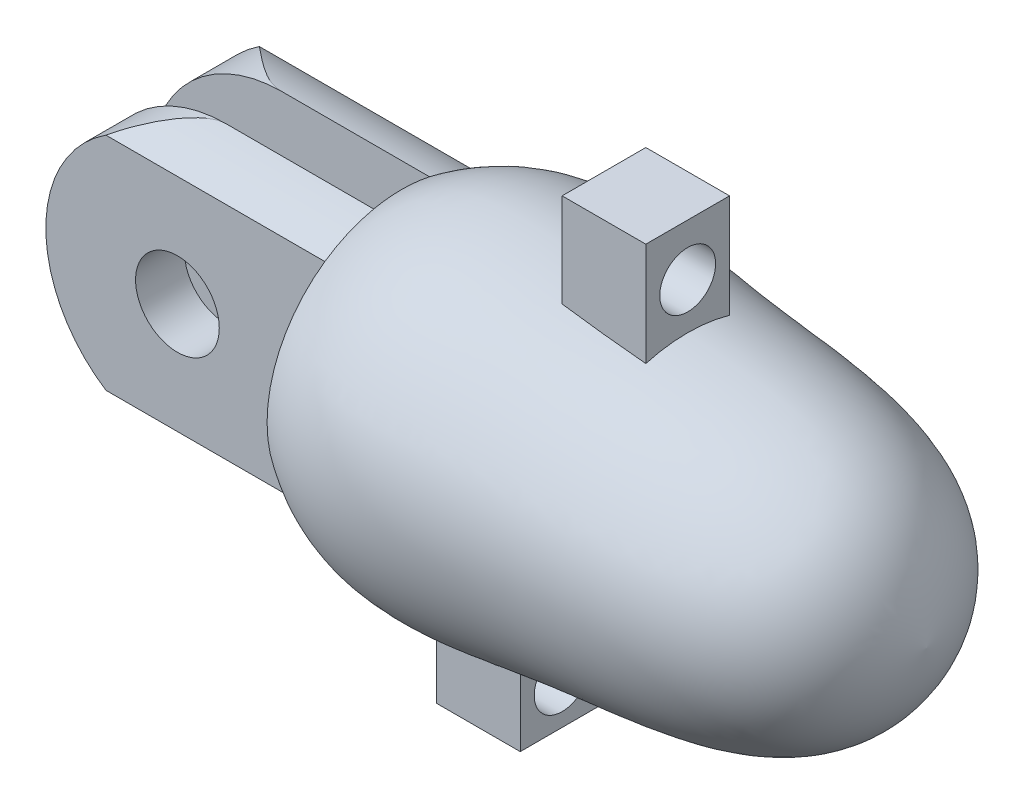
SolidWorks part; units mm, degrees
ref_plane "Front" through (0, 0, 0) normal (0, 0, 1) x (1, 0, 0)
ref_plane "Top" through (0, 0, 0) normal (0, 1, 0) x (1, 0, 0)
ref_plane "Right" through (0, 0, 0) normal (1, 0, 0) x (0, 0, -1)
sketch "Sketch1" plane through (0, 0, 0) normal (0, 0, 1) x (1, 0, 0)
  line L0 (-34.2752, 0) -> (65.3865, 0) construction
  line L1 (-17.5039, 9.6421) -> (-17.5039, 0)
  line L2 (-17.5039, 0) -> (20.1151, 0)
  spline S0 degree 3 poles (-17.5039, 9.6421) (-12.038, 13.468) (1.7207, 9.9869) (18.6749, 10.7604) (20.1151, 0) knots 0 0 0 0 0.417252 1 1 1 1
revolve "Revolve1" add sketch "Sketch1" angle 360 about L0
sketch "Sketch2" plane through (-17.5039, 0, 0) normal (-1, 0, 0) x (0, 0, 1)
  line L1 (-5.5, 10) -> (5.5, 10)
  line L2 (-5.5, 10) -> (-5.5, -10)
  line L3 (-5.5, -10) -> (5.5, -10)
  line L4 (5.5, 10) -> (5.5, -10)
  line L5 (-5.5, 10) -> (5.5, -10) construction
  line L6 (-5.5, -10) -> (5.5, 10) construction
  point P0 (0, 0)
  dimension "D1" = 20
  dimension "D2" = 11
extrude "Boss-Extrude1" add sketch "Sketch2" along normal blind 20
sketch "Sketch3" plane through (-17.5039, 0, 0) normal (-1, 0, 0) x (0, 0, 1)
  circle A0 centre (0, 0) radius 9.6421
  circle A1 centre (0, 0) radius 15
  arc A2 (-5.5, 7.9196) -> (-5.5, -7.9196) centre (0, 0) ccw construction
  dimension "D1" = 30
extrude "Cut-Extrude1" cut sketch "Sketch3" along normal through all
sketch "Sketch4" plane through (0, 0, 0) normal (0, 1, 0) x (1, 0, 0)
  line L0 (-37.5039, 5.5) -> (-37.5039, -5.5) construction
  line L5 (-37.5039, 2) -> (-17.5039, 2)
  line L6 (-37.5039, 2) -> (-37.5039, -2)
  line L7 (-37.5039, -2) -> (-17.5039, -2)
  line L8 (-17.5039, 2) -> (-17.5039, -2)
  line L9 (-17.5039, -5.5) -> (-17.5039, 5.5) construction
  dimension "D1" = 3.5
  dimension "D2" = 3.5
extrude "Cut-Extrude2" cut sketch "Sketch4" against normal through all both and the other way through all
sketch "Sketch6" plane through (0, 0, -2) normal (0, 0, 1) x (1, 0, 0)
  line L0 (-17.5039, -9.4324) -> (-37.5039, -9.4324) construction
  line L1 (-37.5039, 9.4324) -> (-17.5039, 9.4324) construction
  line L2 (-37.5039, -9.4324) -> (-37.5039, 9.4324) construction
  line L3 (-28.0716, -9.4324) -> (-37.5039, -9.4324)
  line L4 (-37.5039, -9.4324) -> (-37.5039, 9.4324)
  line L5 (-37.5039, 9.4324) -> (-28.0716, 9.4324)
  arc A0 (-28.0716, -9.4324) -> (-28.0716, 9.4324) centre (-28.0716, 0) cw
  line M1 (-37.5039, 9.4324) -> (-37.5039, -9.4324)
  line M2 (-37.5039, -9.4324) -> (-17.5039, -9.4324)
  line M4 (-17.5039, 9.4324) -> (-37.5039, 9.4324)
extrude "Cut-Extrude3" cut sketch "Sketch6" against normal through all both and the other way through all contours A0 L4 M2 | A0 M1 M4
sketch "Sketch7" plane through (0, 0, 5.5) normal (0, 0, 1) x (1, 0, 0)
  line L0 (-28.0716, -7.9196) -> (-28.0716, 7.9196) construction
  line L1 (-33.195, -7.9196) -> (-17.5039, -7.9196) construction
  line L2 (-17.5039, 7.9196) -> (-33.195, 7.9196) construction
  circle A0 centre (-28.0716, 0) radius 3
  arc A1 (-33.195, 7.9196) -> (-33.195, -7.9196) centre (-28.0716, 0) ccw construction
  dimension "D1" = 6
extrude "Cut-Extrude4" cut sketch "Sketch7" against normal through all
sketch "Sketch8" plane through (0, 0, 0) normal (0, 1, 0) x (1, 0, 0)
  line L1 (-3, 3) -> (3, 3)
  line L2 (-3, 3) -> (-3, -3)
  line L3 (-3, -3) -> (3, -3)
  line L4 (3, 3) -> (3, -3)
  line L5 (-3, 3) -> (3, -3) construction
  line L6 (-3, -3) -> (3, 3) construction
  point P0 (0, 0)
  dimension "D1" = 6
  dimension "D2" = 6
sketch "Sketch10" plane through (0, 0, 0) normal (0, 1, 0) x (1, 0, 0)
  line L1 (-12, -3) -> (-6, -3)
  line L2 (-12, -3) -> (-12, 3)
  line L3 (-12, 3) -> (-6, 3)
  line L4 (-6, -3) -> (-6, 3)
  line L5 (-12, -3) -> (-6, 3) construction
  line L6 (-12, 3) -> (-6, -3) construction
  point P0 (-9, 0)
  dimension "D1" = 6
  dimension "D2" = 6
  dimension "D3" = 6
extrude "Boss-Extrude3" add sketch "Sketch10" against normal blind 18
sketch "Sketch11" plane through (-6, 0, 0) normal (1, 0, 0) x (0, 0, -1)
  line L0 (0, -18) -> (0, -12.0283) construction
  line L1 (-3, -18) -> (3, -18) construction
  circle A0 centre (0, -15.0142) radius 2
  arc A1 (-3, -11.6482) -> (3, -11.6482) centre (0, 0) ccw construction
  dimension "D1" = 4
extrude "Cut-Extrude6" cut sketch "Sketch11" against normal through all
extrude "Boss-Extrude4" add sketch "Sketch8" along normal blind 18
sketch "Sketch12" plane through (3, 0, 0) normal (1, 0, 0) x (0, 0, -1)
  line L0 (3, 18) -> (3, 10.5879) construction
  line L1 (-3, 18) -> (3, 18) construction
  circle A0 centre (0, 14.294) radius 2
  point P4 (3, 14.294)
  point P7 (0, 18)
  dimension "D1" = 4
extrude "Cut-Extrude7" cut sketch "Sketch12" against normal through all
scale "Scale1" scale about centroid uniform scaling yes scale factor 0.75
